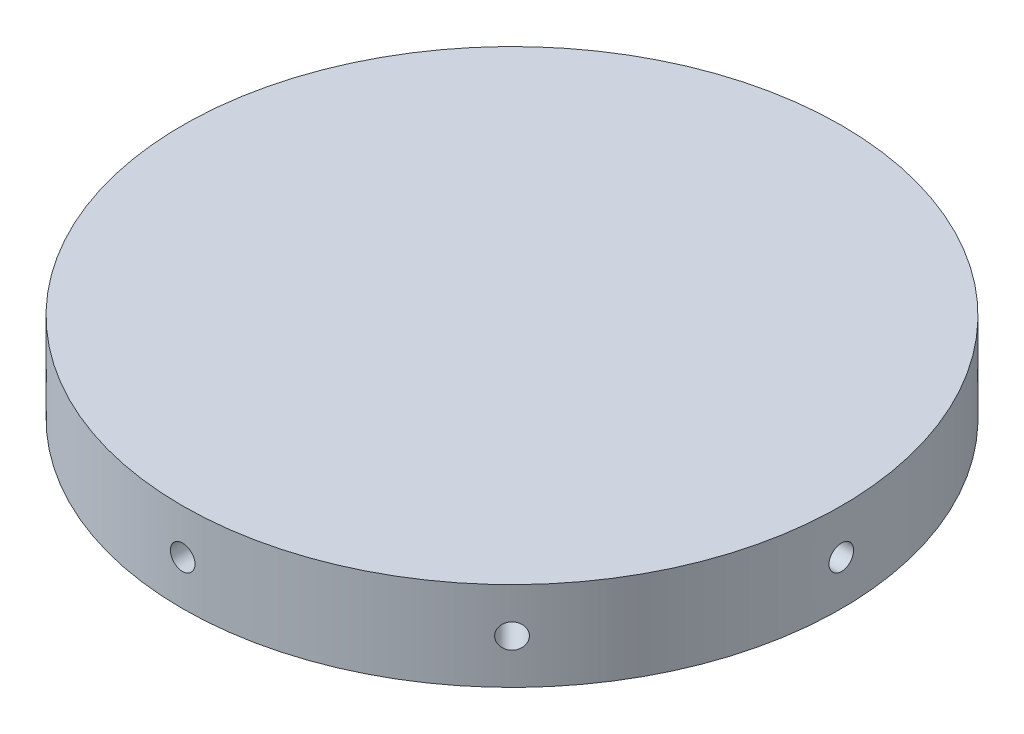
SolidWorks part; units mm, degrees
material "6061 Alloy"
ref_plane "Front Plane" through (0, 0, 0) normal (0, 0, 1) x (1, 0, 0)
ref_plane "Top Plane" through (0, 0, 0) normal (0, 1, 0) x (1, 0, 0)
ref_plane "Right Plane" through (0, 0, 0) normal (1, 0, 0) x (0, 0, -1)
sketch "Sketch1" plane through (0, 0, 0) normal (0, 1, 0) x (1, 0, 0)
  circle A0 centre (0, 0) radius 46.99
  dimension "D1" = 93.98
extrude "Boss-Extrude1" add sketch "Sketch1" along normal blind 12.7
ref_plane "Plane1" through (0, 0, 46.99) normal (0, 0, 1) x (1, 0, 0)
sketch "Sketch2" plane through (0, 0, 46.99) normal (0, 0, 1) x (1, 0, 0)
  line L0 (0, 12.7) -> (0, 0) construction
  line L1 (46.99, 12.7) -> (-46.99, 12.7) construction
  circle A0 centre (0, 6.35) radius 1.7526
  dimension "D1" = 3.5052
extrude "Cut-Extrude1" cut sketch "Sketch2" against normal blind 19.05
pattern_circular "CirPattern1" count 8 over 360 about axis through (0, 0, 0) along (0, 1, 0) of "Cut-Extrude1"
